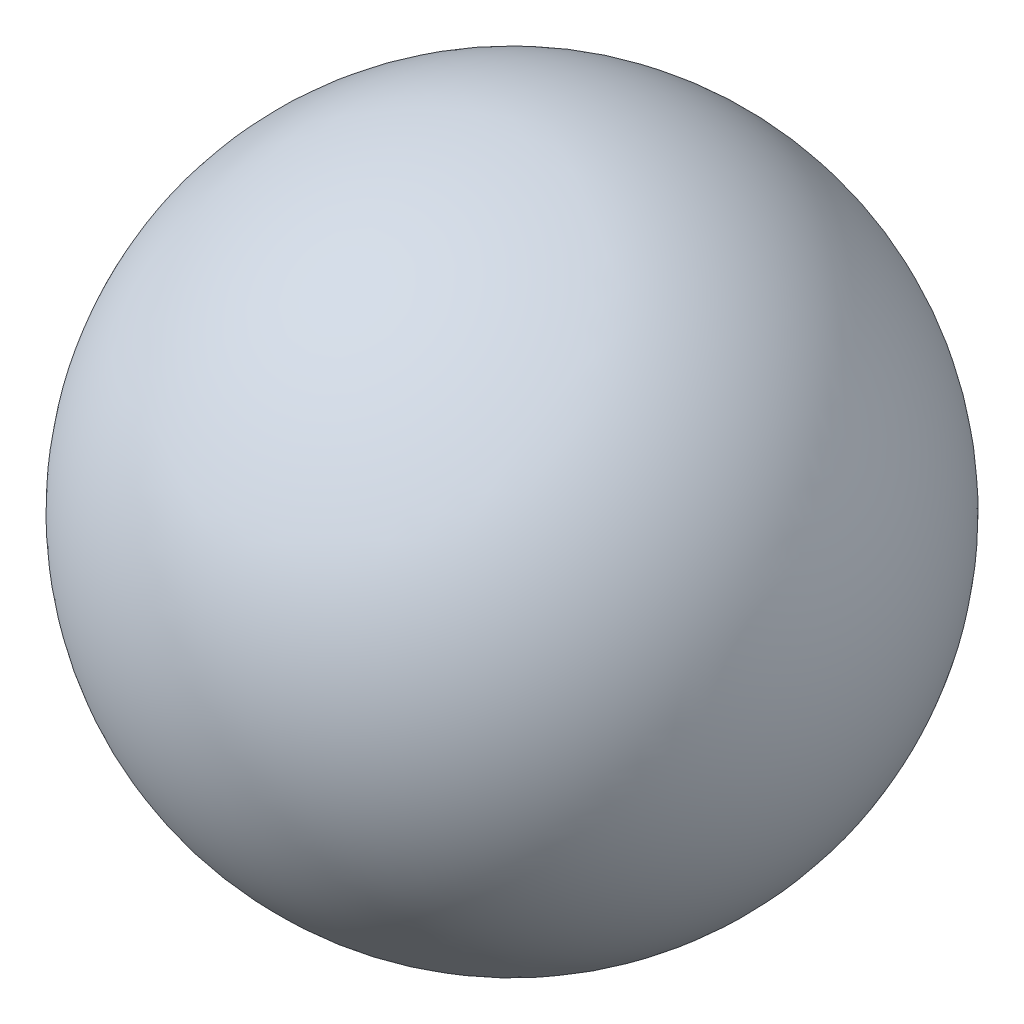
SolidWorks part; units mm, degrees
ref_plane "Front Plane" through (0, 0, 0) normal (0, 0, 1) x (1, 0, 0)
ref_plane "Top Plane" through (0, 0, 0) normal (0, 1, 0) x (1, 0, 0)
ref_plane "Right Plane" through (0, 0, 0) normal (1, 0, 0) x (0, 0, -1)
sketch "Sketch6" plane through (0, 0, 0) normal (0, 1, 0) x (1, 0, 0)
  line L0 (-20, 0) -> (20, 0)
  arc A0 (-20, 0) -> (20, 0) centre (0, 0) ccw
  point P1 (0, 0)
  point P5 (0, 0)
  dimension "D1" = 40
sketch "Sketch7" plane through (0, 0, 0) normal (0, 1, 0) x (1, 0, 0)
  line L0 (0, 0) -> (-19.6, 0)
  line L1 (-19.6, 0) -> (19.6, 0)
  arc A0 (-19.6, 0) -> (19.6, 0) centre (0, 0) ccw
  dimension "D1" = 39.2
revolve "Revolve5" add sketch "Sketch6" angle 360 about L0
revolve "Cut-Revolve16" cut sketch "Sketch7" angle 360 about L0
